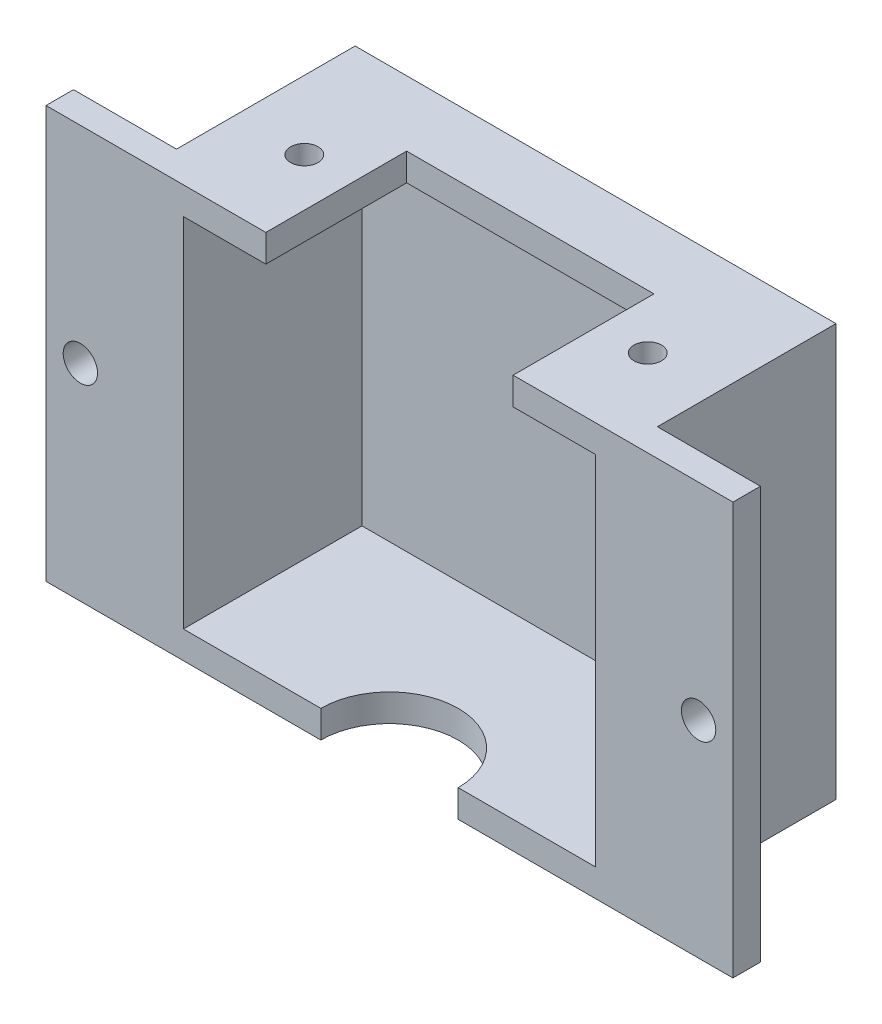
SolidWorks part; units mm, degrees
material "ABS"
ref_plane "Front" through (0, 0, 0) normal (0, 0, 1) x (1, 0, 0)
ref_plane "Top" through (0, 0, 0) normal (0, 1, 0) x (1, 0, 0)
ref_plane "Right" through (0, 0, 0) normal (1, 0, 0) x (0, 0, -1)
sketch "Эскиз1" plane through (0, 0, 0) normal (0, 0, 1) x (1, 0, 0)
  line L1 (-25, 15) -> (25, 15)
  line L2 (-25, 15) -> (-25, -15)
  line L3 (-25, -15) -> (25, -15)
  line L4 (25, 15) -> (25, -15)
  line L5 (-25, 15) -> (25, -15) construction
  line L6 (-25, -15) -> (25, 15) construction
  point P0 (0, 0)
  dimension "D1" = 50
  dimension "D2" = 30
extrude "Бобышка-Вытянуть1" add sketch "Эскиз1" along normal blind 15
sketch "Эскиз2" plane through (0, 15, 0) normal (0, 1, 0) x (1, 0, 0)
  line L0 (25, -15) -> (-25, -15) construction
  line L1 (-9, -15) -> (9, -15)
  line L2 (-9, -15) -> (-9, -4.75)
  line L3 (-9, -4.75) -> (9, -4.75)
  line L4 (9, -15) -> (9, -4.75)
  line L5 (-25, -15) -> (-25, 0) construction
  dimension "D1" = 18
  dimension "D2" = 10.25
  dimension "D3" = 16
extrude "Вырез-Вытянуть1" cut sketch "Эскиз2" against normal blind 5
sketch "Эскиз3" plane through (0, 0, 15) normal (0, 0, 1) x (1, 0, 0)
  line L1 (-15, 13) -> (15, 13)
  line L2 (-15, 13) -> (-15, -13)
  line L3 (-15, -13) -> (15, -13)
  line L4 (15, 13) -> (15, -13)
  line L5 (-15, 13) -> (15, -13) construction
  line L6 (-15, -13) -> (15, 13) construction
  point P0 (0, 0)
  dimension "D1" = 30
  dimension "D2" = 26
extrude "Вырез-Вытянуть2" cut sketch "Эскиз3" against normal blind 13
sketch "Эскиз4" plane through (0, 15, 0) normal (0, 1, 0) x (1, 0, 0)
  line L1 (-25, 0) -> (-17.5, 0)
  line L2 (-25, 0) -> (-25, -13)
  line L3 (-25, -13) -> (-17.5, -13)
  line L4 (-17.5, 0) -> (-17.5, -13)
  dimension "D1" = 13
  dimension "D2" = 7.5
extrude "Вырез-Вытянуть3" cut sketch "Эскиз4" against normal blind 50
sketch "Эскиз5" plane through (0, 15, 0) normal (0, 1, 0) x (1, 0, 0)
  line L1 (25, 0) -> (17.5, 0)
  line L2 (25, 0) -> (25, -13)
  line L3 (25, -13) -> (17.5, -13)
  line L4 (17.5, 0) -> (17.5, -13)
  dimension "D1" = 7.5
  dimension "D2" = 13
extrude "Вырез-Вытянуть4" cut sketch "Эскиз5" against normal blind 50
sketch "Эскиз6" plane through (0, -15, 0) normal (0, -1, 0) x (1, 0, 0)
  line L0 (-5, 15) -> (5, 15)
  line L1 (-25, 15) -> (25, 15) construction
  arc A0 (-5, 15) -> (5, 15) centre (0, 15) ccw
  dimension "D2" = 5
  dimension "D1" = 10
  dimension "D3" = 25
extrude "Вырез-Вытянуть5" cut sketch "Эскиз6" against normal blind 50
sketch "Эскиз7" plane through (0, 0, 15) normal (0, 0, 1) x (1, 0, 0)
  line L0 (25, -15) -> (25, 15) construction
  line L1 (25, 15) -> (9, 15) construction
  circle A0 centre (22.5, 0) radius 1.25
  dimension "D1" = 2.5
  dimension "D2" = 15
extrude "Вырез-Вытянуть6" cut sketch "Эскиз7" against normal blind 50
pattern_linear "Линейный массив1" count 2 spacing 45 along (-1, 0, 0) of "Вырез-Вытянуть6"
sketch "Эскиз8" plane through (0, 15, 0) normal (0, 1, 0) x (1, 0, 0)
  line L0 (-9, -15) -> (-25, -15) construction
  circle A0 centre (-12.5, -8.7) radius 1
  dimension "D1" = 12.5
  dimension "D2" = 6.3
extrude "Вырез-Вытянуть7" cut sketch "Эскиз8" against normal blind 5
pattern_linear "Линейный массив2" count 2 spacing 25 along (1, 0, 0) of "Вырез-Вытянуть7"
